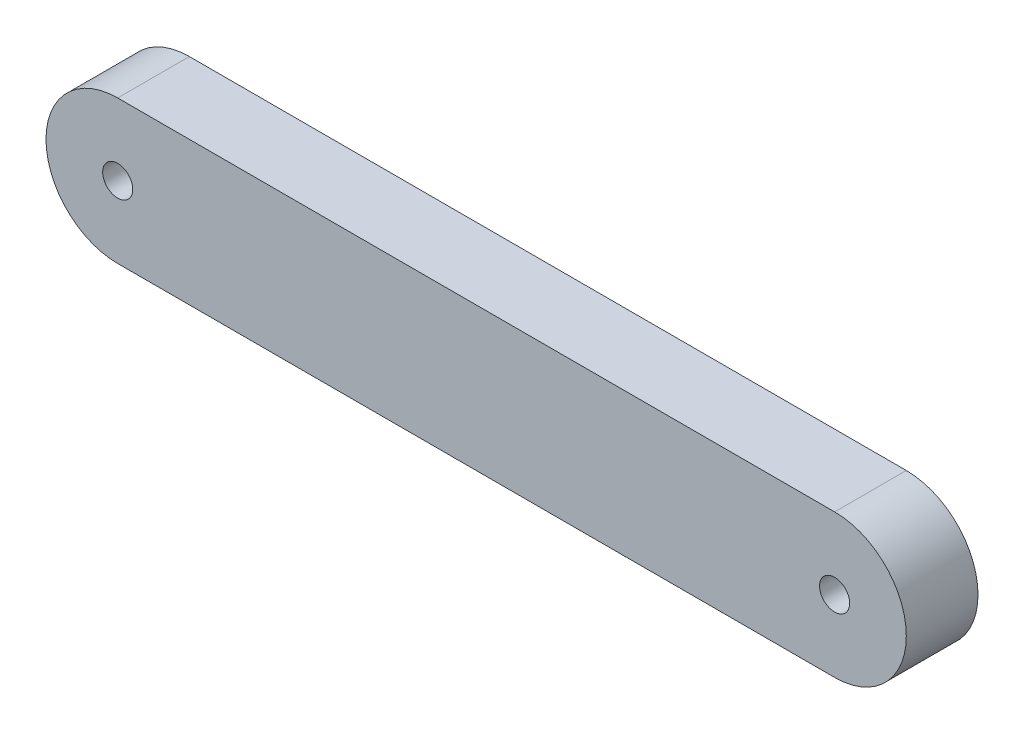
SolidWorks part; units mm, degrees
ref_plane "正面" through (0, 0, 0) normal (0, 0, 1) x (1, 0, 0)
ref_plane "平面" through (0, 0, 0) normal (0, 1, 0) x (1, 0, 0)
ref_plane "右側面" through (0, 0, 0) normal (1, 0, 0) x (0, 0, -1)
sketch "ｽｹｯﾁ1" plane through (0, 0, 0) normal (0, 0, 1) x (1, 0, 0)
  line L1 (-25, -5) -> (25, -5)
  line L2 (-25, -5) -> (-25, 5)
  line L3 (-25, 5) -> (25, 5)
  line L4 (25, -5) -> (25, 5)
  line L5 (-25, -5) -> (25, 5) construction
  line L6 (-25, 5) -> (25, -5) construction
  circle A0 centre (-25, 0) radius 5
  circle A1 centre (25, 0) radius 5
  point P0 (0, 0)
  dimension "D1" = 10
  dimension "D2" = 50
extrude "ﾎﾞｽ - 押し出し1" add sketch "ｽｹｯﾁ1" along normal blind 5 contours L2 A0 | L2 A0 | A1 L3 A0 L1 | L4 A1 | L4 A1
sketch "ｽｹｯﾁ5" plane through (0, 0, 0) normal (0, 0, 1) x (1, 0, 0)
  circle A0 centre (25, 0) radius 1.05
  circle A1 centre (-25, 0) radius 1.05
  dimension "D1" = 2.1
  dimension "D2" = 2.1
extrude "ｶｯﾄ - 押し出し3" cut sketch "ｽｹｯﾁ5" along normal through all both and the other way through all contours A1 | A0
sketch "ｽｹｯﾁ2" plane through (0, 0, 0) normal (0, 1, 0) x (1, 0, 0)
  line L0 (-15, 0) -> (-15, 20)
  line L1 (-25, 0) -> (25, 0) construction
  line L2 (-15, 20) -> (-10, 20)
  line L3 (-10, 20) -> (-10, 0)
  line L4 (-10, 0) -> (-15, 0)
  line L5 (10, 20) -> (10, 0)
  line L6 (10, 0) -> (15, 0)
  line L7 (15, 0) -> (15, 20)
  line L8 (15, 20) -> (10, 20)
  dimension "D1" = 10
  dimension "D2" = 10
  dimension "D3" = 5
  dimension "D4" = 5
  dimension "D5" = 20
  dimension "D6" = 20
sketch "ｽｹｯﾁ3" plane through (0, 0, 0) normal (0, 0, 1) x (1, 0, 0)
  circle A0 centre (-25, 0) radius 1.05
  circle A1 centre (25, 0) radius 1.05
  dimension "D1" = 2.1
  dimension "D2" = 2.1
